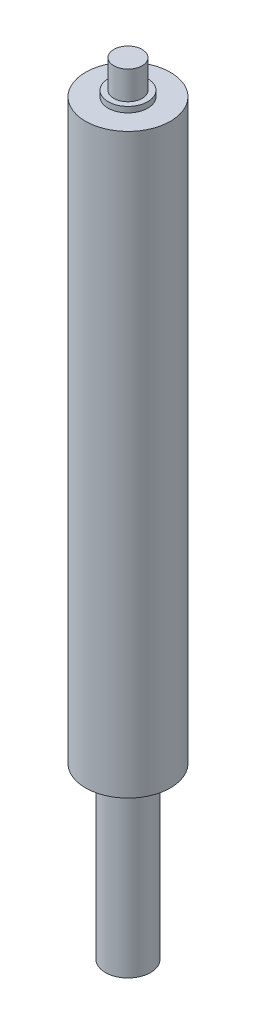
SolidWorks part; units mm, degrees
ref_plane "Front Plane" through (0, 0, 0) normal (0, 0, 1) x (1, 0, 0)
ref_plane "Top Plane" through (0, 0, 0) normal (0, 1, 0) x (1, 0, 0)
ref_plane "Right Plane" through (0, 0, 0) normal (1, 0, 0) x (0, 0, -1)
sketch "Sketch1" plane through (0, 0, 0) normal (0, 1, 0) x (1, 0, 0)
  circle A0 centre (0, 0) radius 7.5
  dimension "D1" = 15
extrude "Boss-Extrude1" add sketch "Sketch1" along normal blind 102
sketch "Sketch2" plane through (0, 0, 0) normal (0, -1, 0) x (1, 0, 0)
  circle A0 centre (0, 0) radius 5
  dimension "D1" = 10
extrude "Boss-Extrude2" add sketch "Sketch2" along normal blind 1
sketch "Sketch3" plane through (0, -1, 0) normal (0, -1, 0) x (1, 0, 0)
  circle A0 centre (0, 0) radius 4
  dimension "D1" = 8
extrude "Boss-Extrude3" add sketch "Sketch3" along normal blind 29
sketch "Sketch4" plane through (0, 102, 0) normal (0, 1, 0) x (1, 0, 0)
  circle A0 centre (0, 0) radius 3.5
  dimension "D1" = 7
extrude "Boss-Extrude4" add sketch "Sketch4" along normal blind 1
sketch "Sketch5" plane through (0, 103, 0) normal (0, 1, 0) x (1, 0, 0)
  circle A0 centre (0, 0) radius 2.5
  dimension "D1" = 5
extrude "Boss-Extrude5" add sketch "Sketch5" along normal blind 5
